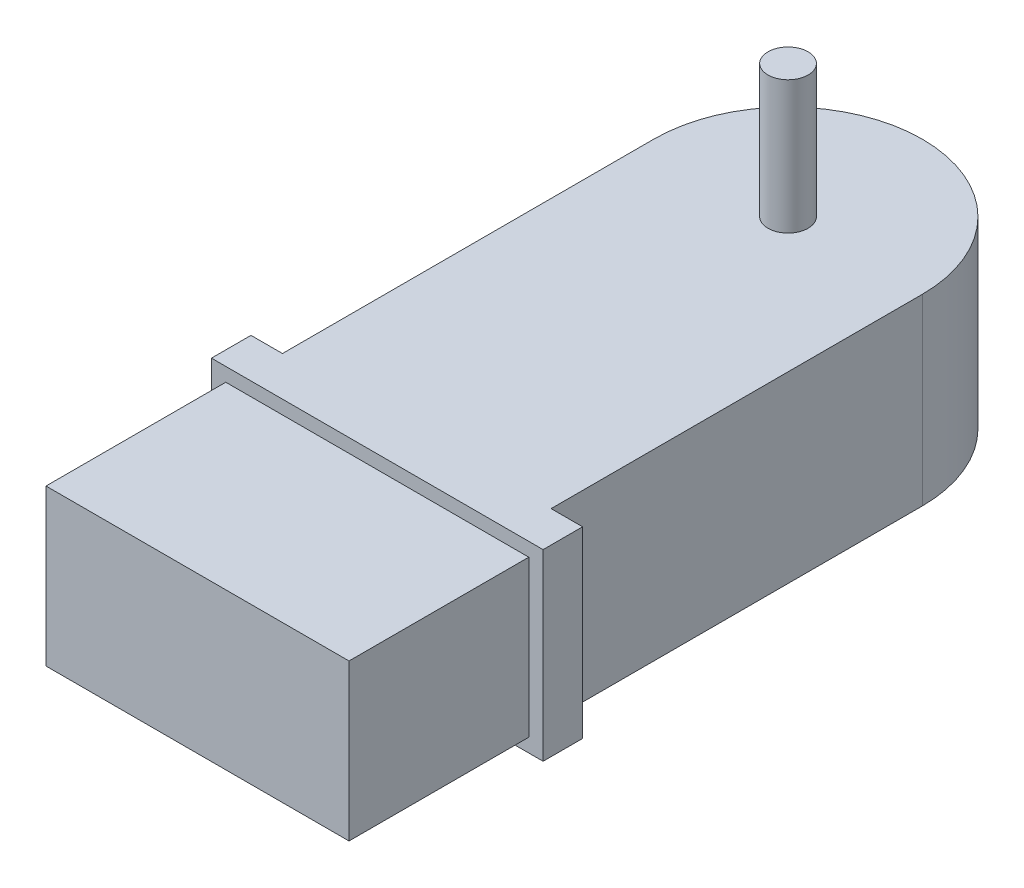
SolidWorks part; units mm, degrees
ref_plane "Front Plane" through (0, 0, 0) normal (0, 0, 1) x (1, 0, 0)
ref_plane "Top Plane" through (0, 0, 0) normal (0, 1, 0) x (1, 0, 0)
ref_plane "Right Plane" through (0, 0, 0) normal (1, 0, 0) x (0, 0, -1)
sketch "Sketch1" plane through (0, 0, 0) normal (0, 1, 0) x (1, 0, 0)
  line L0 (0, 25.3429) -> (14.4391, 25.3429) construction
  line L1 (-10.0203, 15.3226) -> (10.0203, 15.3226)
  line L2 (-10.0203, 15.3226) -> (-10.0203, -15.3225)
  line L3 (-10.0203, -15.3225) -> (10.0203, -15.3225)
  line L4 (10.0203, 15.3226) -> (10.0203, -15.3225)
  line L5 (-10.0203, 15.3226) -> (10.0203, -15.3225) construction
  line L6 (-10.0203, -15.3225) -> (10.0203, 15.3226) construction
  line L8 (-12.3698, -15.3225) -> (12.3698, -15.3225)
  line L9 (-12.3698, -15.3225) -> (-12.3698, -12.3761)
  line L10 (-12.3698, -12.3761) -> (12.3698, -12.3761)
  line L11 (12.3698, -15.3225) -> (12.3698, -12.3761)
  arc A0 (-10.0203, 15.3226) -> (10.0203, 15.3226) centre (0, 15.3226) cw
  point P0 (0, 0)
  point P13 (0, -12.3761)
  point P14 (0, -12.3761)
  point P15 (-0.0145, 15.0906)
  point P16 (-34.1016, -38.5726)
  dimension "D2" = 40.6654
  dimension "D1" = 20.0406
  dimension "D3" = 24.7396
  dimension "D4" = 2.9464
extrude "Boss-Extrude1" add sketch "Sketch1" along normal blind 13.6779 contours L2 L10 L4 L1 | L10 L2 L3 L4 | L10 L9 L8 L2 | L8 L11 L10 L4 | A0 L1
sketch "Sketch2" plane through (0, 0, 15.3225) normal (0, 0, 1) x (1, 0, 0)
  line L0 (0, 13.6779) -> (0, 0) construction
  line L1 (-11.303, 12.6555) -> (11.303, 12.6555)
  line L2 (-11.303, 12.6555) -> (-11.303, 1.0224)
  line L3 (-11.303, 1.0224) -> (11.303, 1.0224)
  line L4 (-12.3698, 0) -> (12.3698, 0)
  line L5 (12.3698, 0) -> (12.3698, 13.6779)
  line L6 (12.3698, 13.6779) -> (-12.3698, 13.6779)
  line L7 (-12.3698, 13.6779) -> (-12.3698, 0)
  line L8 (-12.3698, 0) -> (12.3698, 0)
  line L9 (12.3698, 0) -> (12.3698, 13.6779)
  line L10 (12.3698, 13.6779) -> (-12.3698, 13.6779)
  line L11 (-12.3698, 13.6779) -> (-12.3698, 0)
  line L12 (11.303, 12.6555) -> (11.303, 1.0224)
  line L13 (-11.303, 12.6555) -> (11.303, 1.0224) construction
  line L14 (-11.303, 1.0224) -> (11.303, 12.6555) construction
  line L15 (-12.3698, 6.8389) -> (12.3698, 6.8389) construction
  point P2 (0, 6.8389)
  point P14 (0, 6.8389)
  point P15 (0, 6.8389)
  dimension "D2" = 11.6332
  dimension "D3" = 22.606
  dimension "D1" = 0
extrude "Boss-Extrude2" add sketch "Sketch2" along normal blind 13.4112 contours L12 L1 L2 L3
sketch "Sketch3" plane through (0, 13.6779, 0) normal (0, 1, 0) x (1, 0, 0)
  line L7 (-10.0203, 15.3226) -> (-10.0203, -12.3761)
  line L8 (-10.0203, -12.3761) -> (-12.3698, -12.3761)
  line L9 (-12.3698, -12.3761) -> (-12.3698, -15.3225)
  line L10 (-12.3698, -15.3225) -> (12.3698, -15.3225)
  line L11 (12.3698, -15.3225) -> (12.3698, -12.3761)
  line L12 (12.3698, -12.3761) -> (10.0203, -12.3761)
  line L13 (10.0203, -12.3761) -> (10.0203, 15.3226)
  line L14 (-10.0203, 15.3226) -> (-10.0203, -12.3761)
  line L15 (-10.0203, -12.3761) -> (-12.3698, -12.3761)
  line L16 (-12.3698, -12.3761) -> (-12.3698, -15.3225)
  line L17 (-12.3698, -15.3225) -> (12.3698, -15.3225)
  line L18 (12.3698, -15.3225) -> (12.3698, -12.3761)
  line L19 (12.3698, -12.3761) -> (10.0203, -12.3761)
  line L20 (10.0203, -12.3761) -> (10.0203, 15.3226)
  circle A0 centre (0, 15.3226) radius 1.4986
  arc A1 (10.0203, 15.3226) -> (-10.0203, 15.3226) centre (0, 15.3226) ccw
  arc A2 (10.0203, 15.3226) -> (-10.0203, 15.3226) centre (0, 15.3226) ccw
  dimension "D2" = 2.9972
  dimension "D1" = 0
extrude "Boss-Extrude3" add sketch "Sketch3" along normal blind 9.906 contours A0
